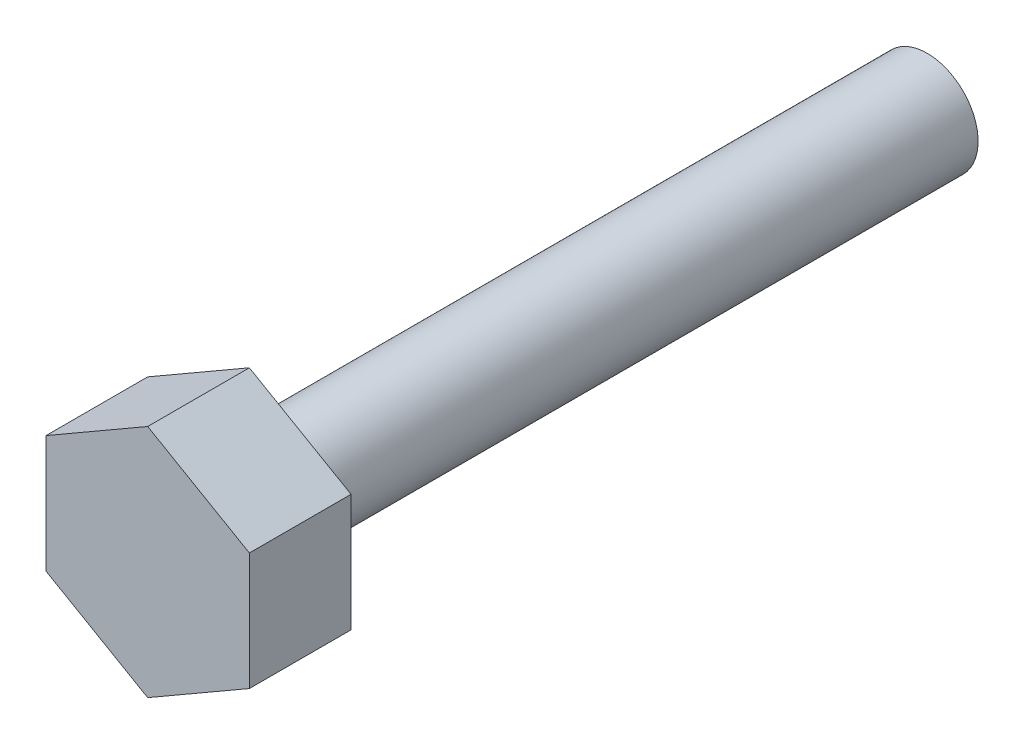
SolidWorks part; units mm, degrees
material "AISI 1020 Steel, Cold Rolled"
ref_plane "Front Plane" through (0, 0, 0) normal (0, 0, 1) x (1, 0, 0)
ref_plane "Top Plane" through (0, 0, 0) normal (0, 1, 0) x (1, 0, 0)
ref_plane "Right Plane" through (0, 0, 0) normal (1, 0, 0) x (0, 0, -1)
sketch "Sketch4" plane through (0, 0, 0) normal (0, 0, 1) x (1, 0, 0)
  line L1 (0, 6.9282) -> (-6, 3.4641)
  line L2 (-6, 3.4641) -> (-6, -3.4641)
  line L3 (-6, -3.4641) -> (0, -6.9282)
  line L4 (0, -6.9282) -> (6, -3.4641)
  line L5 (6, -3.4641) -> (6, 3.4641)
  line L6 (6, 3.4641) -> (0, 6.9282)
  circle A0 centre (0, 0) radius 6 construction
  dimension "D1" = 12
extrude "Boss-Extrude2" add sketch "Sketch4" along normal mid plane 6
sketch "Sketch5" plane through (0, 0, -3) normal (0, 0, -1) x (-1, 0, 0)
  line L6 (0, 6.9282) -> (-6, 3.4641)
  line L7 (-6, 3.4641) -> (-6, -3.4641)
  line L8 (-6, -3.4641) -> (0, -6.9282)
  line L9 (0, -6.9282) -> (6, -3.4641)
  line L10 (6, -3.4641) -> (6, 3.4641)
  line L11 (6, 3.4641) -> (0, 6.9282)
  line L12 (0, 6.9282) -> (-6, 3.4641)
  line L13 (-6, 3.4641) -> (-6, -3.4641)
  line L14 (-6, -3.4641) -> (0, -6.9282)
  line L15 (0, -6.9282) -> (6, -3.4641)
  line L16 (6, -3.4641) -> (6, 3.4641)
  line L17 (6, 3.4641) -> (0, 6.9282)
  circle A0 centre (0, 0) radius 3
  dimension "D2" = 6
  dimension "D1" = 0
extrude "Boss-Extrude3" add sketch "Sketch5" along normal blind 40 contours A0
